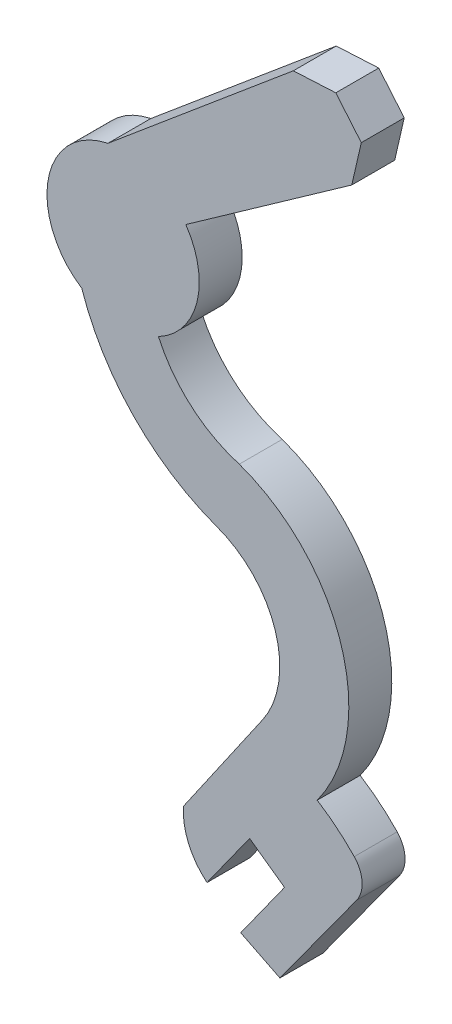
SolidWorks part; units mm, degrees
ref_plane "Front" through (0, 0, 0) normal (0, 0, 1) x (1, 0, 0)
ref_plane "Top" through (0, 0, 0) normal (0, 1, 0) x (1, 0, 0)
ref_plane "Right" through (0, 0, 0) normal (1, 0, 0) x (0, 0, -1)
sketch "Sketch1" plane through (0, 0, 0) normal (0, 0, 1) x (1, 0, 0)
  line L0 (1209.4518, 108.0989) -> (1211.2336, 105.9744)
  line L2 (1193.5257, 97.0802) -> (1206.4842, 107.9484)
  line L3 (1205.5474, 52.5806) -> (1210.9113, 59.9701)
  line L4 (1202.809, 53.9474) -> (1205.5474, 52.5806)
  line L5 (1204.3195, 67.5766) -> (1198.8053, 59.601)
  line L6 (1205.8681, 58.2226) -> (1203.4284, 59.9684)
  line L7 (1202.809, 53.9474) -> (1205.8681, 58.2226)
  line L8 (1203.4284, 59.9684) -> (1200.4516, 55.8083)
  line L9 (1198.9698, 94.8876) -> (1210.5686, 103.0783)
  line L10 (1210.5686, 103.0783) -> (1211.2336, 105.9744)
  line L11 (1206.4842, 107.9484) -> (1209.4518, 108.0989)
  arc A0 (1193.5257, 97.0802) -> (1191.7005, 87.3991) centre (1194.5896, 91.867) ccw
  arc A1 (1208.1532, 64.6426) -> (1202.706, 82.2552) centre (1198.8686, 71.4198) ccw
  arc A2 (1191.7005, 87.3991) -> (1201.0951, 77.7066) centre (1206.5557, 92.3986) ccw
  arc A3 (1198.8053, 59.601) -> (1200.4516, 55.8083) centre (1203.3365, 59.3142) ccw
  arc A4 (1210.9113, 59.9701) -> (1210.7418, 62.5234) centre (1209.2927, 61.145) ccw
  arc A5 (1210.7418, 62.5234) -> (1208.1532, 64.6426) centre (1200.9714, 53.229) ccw
  arc A6 (1204.3195, 67.5766) -> (1201.0951, 77.7066) centre (1198.8686, 71.4198) ccw
  arc A7 (1197.059, 87.1541) -> (1198.9698, 94.8876) centre (1194.5896, 91.867) ccw
  arc A8 (1197.059, 87.1541) -> (1202.706, 82.2552) centre (1205.2049, 90.8399) ccw
  dimension "D1" = 3
extrude "Base-Extrude" add sketch "Sketch1" along normal blind 3
